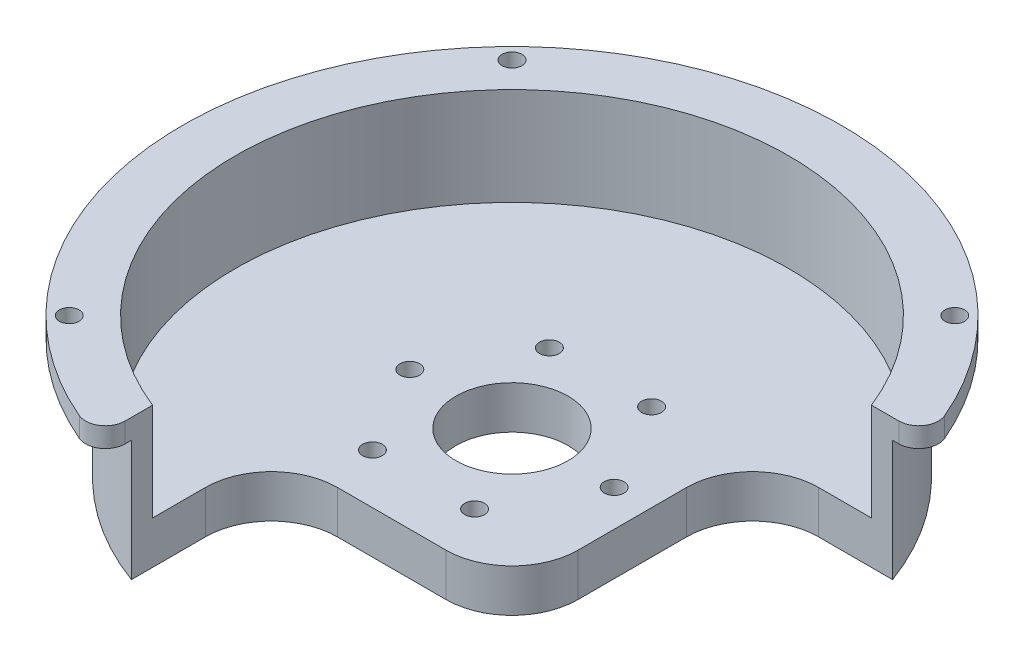
SolidWorks part; units mm, degrees
ref_plane "Front Plane" through (0, 0, 0) normal (0, 0, 1) x (1, 0, 0)
ref_plane "Top Plane" through (0, 0, 0) normal (0, 1, 0) x (1, 0, 0)
ref_plane "Right Plane" through (0, 0, 0) normal (1, 0, 0) x (0, 0, -1)
sketch "Sketch1" plane through (0, 0, 0) normal (0, 1, 0) x (1, 0, 0)
  line L0 (-15.5, -31) -> (-15.5, -42.2463)
  line L1 (21, 5.5) -> (21, -11)
  line L2 (0, 0) -> (15.5, 0) construction
  line L3 (-5.5, -21) -> (11, -21)
  line L9 (31, 15.5) -> (42.2463, 15.5)
  line L11 (0, 0) -> (-13.4234, 7.75) construction
  circle A0 centre (0, 0) radius 8.5
  circle A1 centre (-7.75, 13.4234) radius 1.5
  circle A2 centre (7.75, 13.4234) radius 1.5
  circle A3 centre (15.5, 0) radius 1.5
  circle A4 centre (-15.5, 0) radius 1.5
  arc A5 (42.2463, 15.5) -> (-15.5, -42.2463) centre (0, 0) ccw
  circle A7 centre (-7.75, -13.4234) radius 1.5
  circle A8 centre (7.75, -13.4234) radius 1.5
  arc A9 (-15.5, -31) -> (-5.5, -21) centre (-5.5, -31) cw
  arc A10 (31, 15.5) -> (21, 5.5) centre (31, 5.5) ccw
  arc A11 (11, -21) -> (21, -11) centre (11, -11) ccw
  dimension "D9" = 3
  dimension "D11" = 3
  dimension "D13" = 90
  dimension "D2" = 17
  dimension "D15" = 10
extrude "Boss-Extrude1" add sketch "Sketch1" along normal blind 6.5
sketch "Sketch3" plane through (0, 6.5, 0) normal (0, 1, 0) x (1, 0, 0)
  line L0 (42.2463, 15.5) -> (39.0352, 15.5)
  line L1 (31, 15.5) -> (42.2463, 15.5) construction
  line L2 (-15.5, -39.0352) -> (-15.5, -42.2463)
  line L3 (-15.5, -42.2463) -> (-15.5, -31) construction
  arc A0 (39.0352, 15.5) -> (-15.5, -39.0352) centre (0, 0) ccw
  arc A1 (42.2463, 15.5) -> (-15.5, -42.2463) centre (0, 0) ccw
  dimension "D1" = 84
extrude "Boss-Extrude3" add sketch "Sketch3" along normal blind 14.82
sketch "Sketch4" plane through (0, 21.32, 0) normal (0, 1, 0) x (1, 0, 0)
  line L0 (42.2463, 15.5) -> (43.2059, 15.5)
  line L1 (-15.5, -42.2463) -> (-15.5, -43.2059)
  line L2 (0, 0) -> (33.5876, 33.5876) construction
  line L3 (0, 0) -> (-33.5876, 33.5876) construction
  line L4 (0, 0) -> (-33.5876, -33.5876) construction
  arc A0 (42.2463, 15.5) -> (-15.5, -42.2463) centre (0, 0) ccw
  arc A1 (45.9637, 19.6809) -> (-19.6809, -45.9637) centre (0, 0) ccw
  arc A2 (-15.5, -43.2059) -> (-19.6809, -45.9637) centre (-18.5, -43.2059) cw
  arc A3 (43.2059, 15.5) -> (45.9637, 19.6809) centre (43.2059, 18.5) ccw
  circle A4 centre (0, 0) radius 47.5 construction
  circle A6 centre (-33.5876, 33.5876) radius 1.5
  circle A7 centre (-33.5876, -33.5876) radius 1.5
  circle A8 centre (33.5876, 33.5876) radius 1.5
  dimension "D1" = 100
  dimension "D2" = 3
  dimension "D3" = 95
  dimension "D4" = 3
  dimension "D5" = 3
  dimension "D6" = 3
extrude "Boss-Extrude4" add sketch "Sketch4" against normal blind 3
